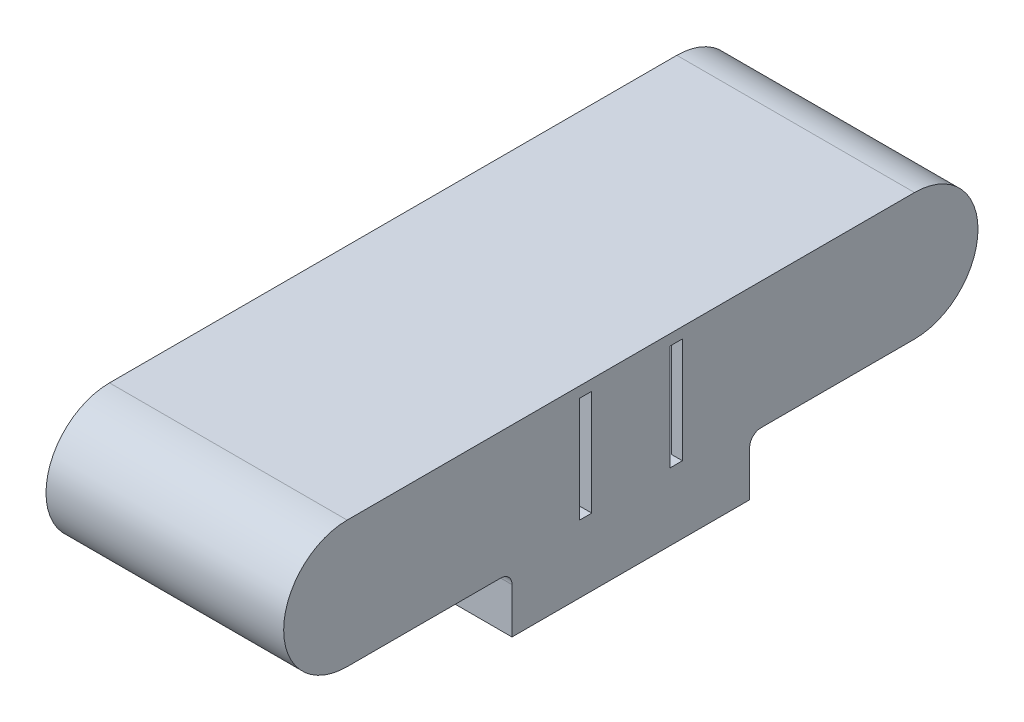
SolidWorks part; units mm, degrees
ref_plane "Front Plane" through (0, 0, 0) normal (0, 0, 1) x (1, 0, 0)
ref_plane "Top Plane" through (0, 0, 0) normal (0, 1, 0) x (1, 0, 0)
ref_plane "Right Plane" through (0, 0, 0) normal (1, 0, 0) x (0, 0, -1)
sketch "Sketch1" plane through (0, 0, 0) normal (1, 0, 0) x (0, 0, -1)
  line L0 (-63.5, 0) -> (63.5, 0) construction
  line L1 (-63.5, 14.211) -> (63.5, 14.211)
  line L4 (-63.5, -14.211) -> (63.5, -14.211)
  line L6 (-55.5973, 11.811) -> (55.5973, 11.811)
  line L8 (-55.5973, -11.811) -> (55.5973, -11.811)
  circle A0 centre (-63.5, 0) radius 11.811
  arc A2 (-63.5, 14.211) -> (-63.5, -14.211) centre (-63.5, 0) ccw
  arc A3 (63.5, -14.211) -> (63.5, 14.211) centre (63.5, 0) ccw
  circle A4 centre (63.5, 0) radius 11.811
  arc A5 (-55.5973, -11.811) -> (-55.5973, 11.811) centre (-63.5, 0) ccw
  arc A6 (55.5973, 11.811) -> (55.5973, -11.811) centre (63.5, 0) ccw
  point P7 (0, 0)
  dimension "D1" = 23.622
  dimension "D3" = 2.4
  dimension "D2" = 127
  dimension "D4" = 2.4
  dimension "D5" = 2.4
extrude "Boss-Extrude1" add sketch "Sketch1" along normal blind 50.8
sketch "Sketch2" plane through (50.8, 0, 0) normal (1, 0, 0) x (0, 0, -1)
  line L0 (-63.5, -14.211) -> (63.5, -14.211) construction
  line L1 (63.5, 14.211) -> (-63.5, 14.211) construction
  line L2 (-63.5, -14.211) -> (63.5, -14.211)
  line L3 (63.5, 14.211) -> (-63.5, 14.211)
  arc A0 (63.5, -14.211) -> (63.5, 14.211) centre (63.5, 0) ccw construction
  arc A1 (-63.5, 14.211) -> (-63.5, -14.211) centre (-63.5, 0) ccw construction
  arc A2 (63.5, -14.211) -> (63.5, 14.211) centre (63.5, 0) ccw
  arc A3 (-63.5, 14.211) -> (-63.5, -14.211) centre (-63.5, 0) ccw
extrude "Boss-Extrude2" add sketch "Sketch2" along normal blind 2.4
sketch "Sketch4" plane through (0, -14.211, 0) normal (0, -1, 0) x (1, 0, 0)
  line L0 (0, 0) -> (53.2, 0) construction
  line L1 (53.2, 63.5) -> (53.2, -63.5) construction
  line L2 (0, 63.5) -> (0, -63.5) construction
  line L5 (0, -26.6) -> (0, 26.6)
  line L6 (53.2, -26.6) -> (0, -26.6)
  line L7 (53.2, -26.6) -> (53.2, 26.6)
  line L8 (53.2, 26.6) -> (0, 26.6)
  line L10 (53.2, -26.6) -> (0, 26.6) construction
  line L11 (53.2, 26.6) -> (0, -26.6) construction
  line L12 (0, 26.6) -> (0, -26.6) construction
  point P6 (26.6, 0)
  point P11 (26.6, 0)
extrude "Boss-Extrude4" add sketch "Sketch4" along normal blind 12.7
sketch "Sketch5" plane through (0, -26.911, 0) normal (0, -1, 0) x (1, 0, 0)
  line L0 (26.6, 63.5) -> (26.6, -63.5) construction
  line L3 (0, 0) -> (53.2, 0) construction
  line L6 (53.2, -63.5) -> (0, -63.5) construction
  line L7 (53.2, 63.5) -> (0, 63.5) construction
  line L8 (53.2, 63.5) -> (53.2, 26.6) construction
  circle A0 centre (26.6, 0) radius 4.7625
  point P5 (26.6, 0)
  point P17 (26.6, -63.5)
  dimension "D1" = 9.525
extrude "Cut-Extrude2" cut sketch "Sketch5" against normal up to next
sketch "Sketch7" plane through (0, -11.811, 0) normal (0, 1, 0) x (1, 0, 0)
  line L0 (0, 63.5) -> (0, -63.5) construction
  line L1 (0, 8.75) -> (53.2, 8.75)
  line L2 (0, 8.75) -> (0, 6.35)
  line L3 (0, 6.35) -> (53.2, 6.35)
  line L4 (53.2, 8.75) -> (53.2, 6.35)
  line L5 (53.2, 63.5) -> (53.2, -63.5) construction
  line L6 (26.6, 6.35) -> (26.6, -6.35) construction
  line L7 (0, -6.35) -> (53.2, -6.35)
  line L8 (0, -6.35) -> (0, -8.75)
  line L9 (0, -8.75) -> (53.2, -8.75)
  line L10 (53.2, -6.35) -> (53.2, -8.75)
  point P14 (26.6, 0)
  dimension "D1" = 12.7
  dimension "D2" = 2.4
extrude "Boss-Extrude5" add sketch "Sketch7" along normal up to surface (23.622 mm away) up to face at (25.4, 11.811, 0)
sketch "Sketch9" plane through (0, 0, 8.75) normal (0, 0, 1) x (1, 0, 0)
  line L0 (6.35, 3.175) -> (44.45, 3.175)
  line L1 (44.45, -3.175) -> (6.35, -3.175)
  line L2 (50.8, -11.811) -> (50.8, 11.811) construction
  arc A0 (6.35, 3.175) -> (6.35, -3.175) centre (6.35, 0) ccw
  arc A1 (44.45, -3.175) -> (44.45, 3.175) centre (44.45, 0) ccw
  dimension "D1" = 6.35
  dimension "D2" = 6.35
  dimension "D3" = 6.35
extrude "Cut-Extrude3" cut sketch "Sketch9" against normal up to surface (17.5 mm away) up to face at (25.4, 0, -8.75)
sketch "Sketch10" plane through (50.8, 0, 0) normal (-1, 0, 0) x (0, 0, 1)
  line L0 (-8.75, -11.811) -> (-55.5973, -11.811) construction
  line L1 (-8.75, 11.811) -> (-11.544, 11.811)
  line L2 (-8.75, 11.811) -> (-8.75, -11.811)
  line L3 (-8.75, -11.811) -> (-11.544, -11.811)
  line L4 (-11.544, 11.811) -> (-11.544, -11.811)
  line L5 (55.5973, -11.811) -> (8.75, -11.811) construction
  line L6 (8.75, 11.811) -> (11.544, 11.811)
  line L7 (8.75, 11.811) -> (8.75, -11.811)
  line L8 (8.75, -11.811) -> (11.544, -11.811)
  line L9 (11.544, 11.811) -> (11.544, -11.811)
  point P14 (0, 0)
  dimension "D1" = 2.794
extrude "Cut-Extrude4" cut sketch "Sketch10" against normal blind 2.54
fillet "Fillet1" radius 2.54 4 edges at (26.6, -14.211, -26.6) (26.6, -14.211, 26.6) (50.8, -11.811, 0) (50.8, 11.811, 0)
equation "\"extrusion_width\"= 0.4mm"
equation "\"D4@Sketch1\"=\"shell_thickness\""
equation "\"D3@Sketch1\"=\"shell_thickness\""
equation "\"D1@Boss-Extrude2\"=\"shell_thickness\""
equation "\"D5@Sketch1\"=\"shell_thickness\""
equation "\"wall_count\"= 3"
equation "\"shell_thickness\"= 2 * \"wall_count\" * \"extrusion_width\""
equation "\"D2@Sketch7\"=\"shell_thickness\""
